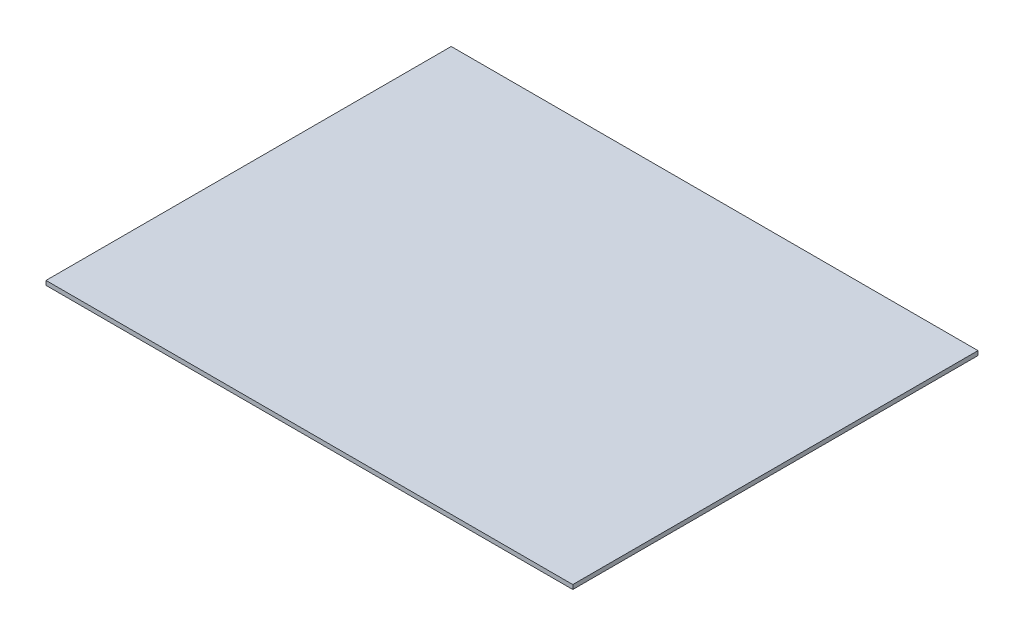
SolidWorks part; units mm, degrees
ref_plane "Front Plane" through (0, 0, 0) normal (0, 0, 1) x (1, 0, 0)
ref_plane "Top Plane" through (0, 0, 0) normal (0, 1, 0) x (1, 0, 0)
ref_plane "Right Plane" through (0, 0, 0) normal (1, 0, 0) x (0, 0, -1)
sketch "Sketch1" plane through (0, 0, 0) normal (0, 0, 1) x (1, 0, 0)
  line L0 (-457.2, 0) -> (457.2, 0) construction
  line L1 (0, -1.016) -> (0, 1.016) construction
  point P5 (0, 0)
  point P9 (0, 0)
  dimension "Width" = 914.4
  dimension "Wire Diameter" = 2.032
sketch "Sketch2" plane through (0, 0, 0) normal (1, 0, 0) x (0, 0, -1)
  line L0 (-152.4, 0) -> (152.4, 0) construction
  point P3 (0, 0)
  dimension "Length" = 304.8
sketch "Sketch3" plane through (0, 0, 0) normal (0, 0, 1) x (1, 0, 0)
  line L1 (-457.2, -1.016) -> (457.2, -1.016)
  line L2 (-457.2, -1.016) -> (-457.2, 1.016)
  line L3 (-457.2, 1.016) -> (457.2, 1.016)
  line L4 (457.2, -1.016) -> (457.2, 1.016)
  line L5 (-457.2, -1.016) -> (457.2, 1.016) construction
  line L6 (-457.2, 1.016) -> (457.2, -1.016) construction
  point P0 (0, 0)
extrude "Boss-Extrude1" add sketch "Sketch3" along normal mid plane 304.8
sketch "Sketch4" plane through (0, 1.016, 0) normal (0, 1, 0) x (1, 0, 0)
  line L1 (-457.2, 152.4) -> (-209.55, 152.4)
  line L2 (-457.2, 152.4) -> (-457.2, -38.1)
  line L3 (-457.2, -38.1) -> (-209.55, -38.1)
  line L4 (-209.55, 152.4) -> (-209.55, -38.1)
  dimension "D1" = 247.65
  dimension "D2" = 190.5
extrude "Cut-Extrude1" cut sketch "Sketch4" against normal through all flip side to cut
equation "\"D1@Boss-Extrude1\"=\"Length@Sketch2\""
